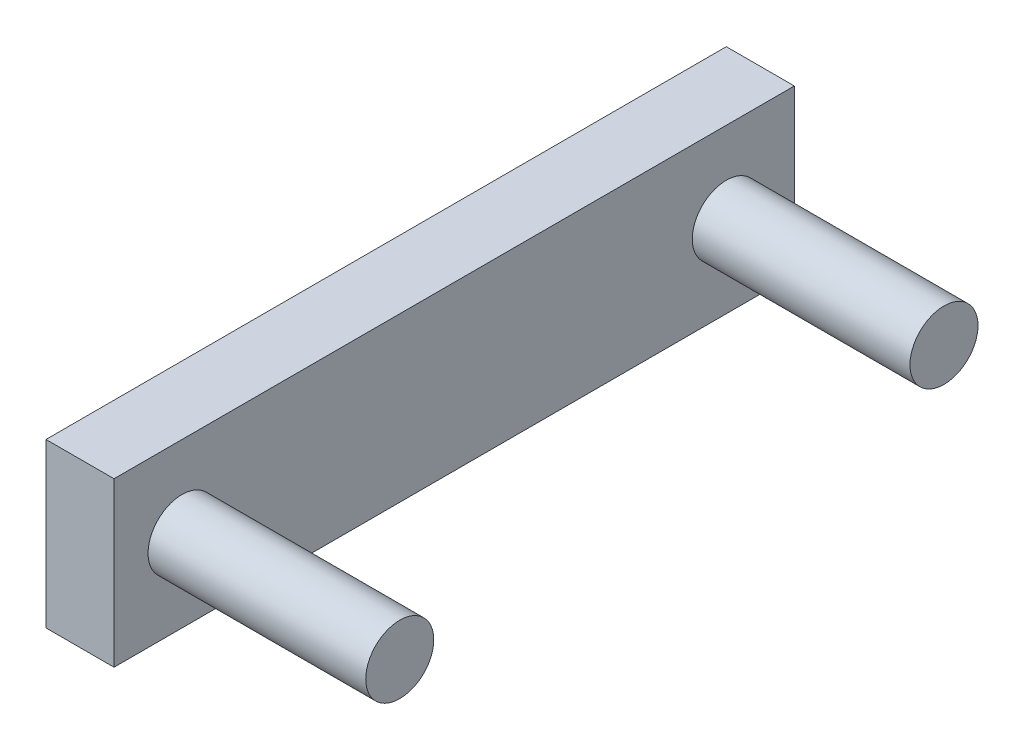
SolidWorks part; units mm, degrees
ref_plane "前视基准面" through (0, 0, 0) normal (0, 0, 1) x (1, 0, 0)
ref_plane "上视基准面" through (0, 0, 0) normal (0, 1, 0) x (1, 0, 0)
ref_plane "右视基准面" through (0, 0, 0) normal (1, 0, 0) x (0, 0, -1)
sketch "草图1" plane through (0, 0, 0) normal (0, 1, 0) x (1, 0, 0)
  line L1 (0, 25) -> (5, 25)
  line L2 (0, 25) -> (0, -25)
  line L3 (0, -25) -> (5, -25)
  line L4 (5, 25) -> (5, -25)
  dimension "D1" = 5
  dimension "D2" = 50
extrude "凸台-拉伸1" add sketch "草图1" along normal blind 12
sketch "草图2" plane through (5, 0, 0) normal (1, 0, 0) x (0, 0, -1)
  line L0 (0, -0.6895) -> (0, 15.1501) construction
  line L2 (-25, 0) -> (25, 0) construction
  circle A0 centre (20, 6) radius 2.5
  circle A1 centre (-20, 6) radius 2.5
  dimension "D1" = 5
  dimension "D2" = 20
  dimension "D3" = 6
extrude "凸台-拉伸2" add sketch "草图2" along normal blind 16
